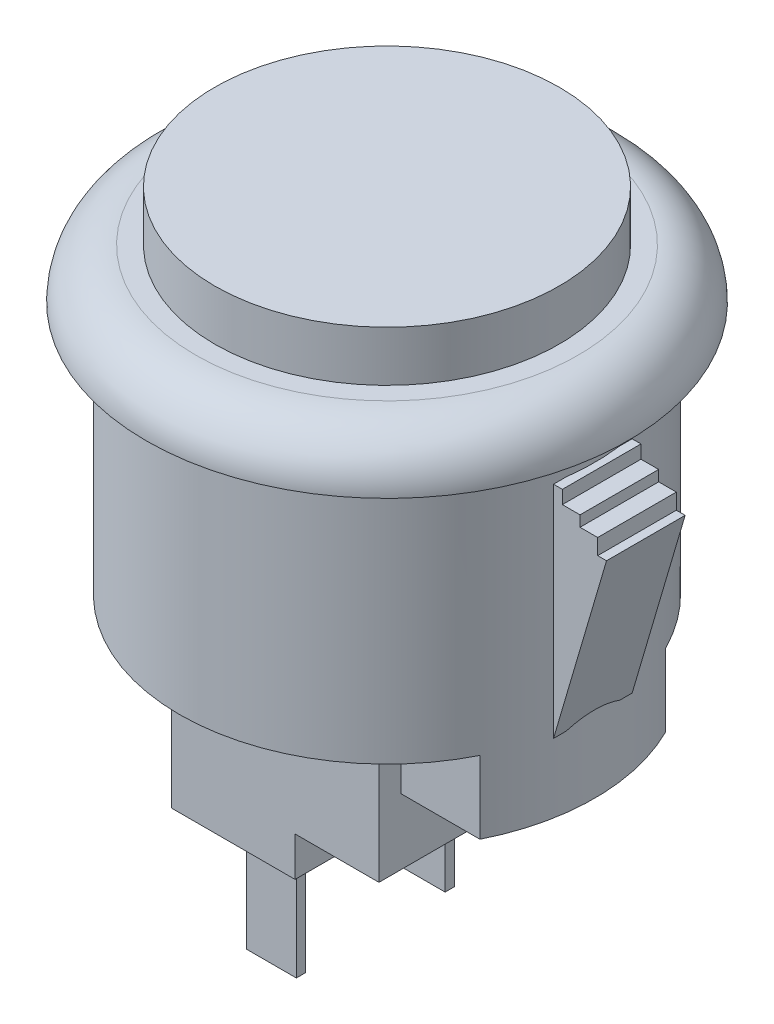
SolidWorks part; units mm, degrees
ref_plane "Front Plane" through (0, 0, 0) normal (0, 0, 1) x (1, 0, 0)
ref_plane "Top Plane" through (0, 0, 0) normal (0, 1, 0) x (1, 0, 0)
ref_plane "Right Plane" through (0, 0, 0) normal (1, 0, 0) x (0, 0, -1)
sketch "Sketch1" plane through (0, 0, 0) normal (0, 0, 1) x (1, 0, 0)
  line L0 (0, 0) -> (-11.75, 0)
  line L1 (-11.75, 0) -> (-11.75, 14.35)
  line L2 (-11.75, 14.35) -> (-13.625, 14.35)
  line L3 (-9.75, 17.15) -> (-9.75, 20)
  line L4 (-9.75, 20) -> (0, 20)
  line L5 (0, 20) -> (0, 0)
  line L6 (0, 0) -> (0, -2.2654) construction
  line L8 (-9.75, 17.15) -> (-10.825, 17.15)
  arc A0 (-13.625, 14.35) -> (-10.825, 17.15) centre (-10.825, 14.35) cw
  dimension "D1" = 23.5
  dimension "D2" = 27.25
  dimension "D3" = 19.5
  dimension "D4" = 14.35
  dimension "D5" = 20
  dimension "D6" = 2.85
revolve "Revolve1" add sketch "Sketch1" angle 360 about L6
sketch "Sketch2" plane through (0, 0, 0) normal (0, 0, 1) x (1, 0, 0)
  line L0 (-5.875, 0) -> (-5.875, -10.23)
  line L1 (-11.75, 0) -> (11.75, 0) construction
  line L2 (-5.875, -10.23) -> (1.125, -10.23)
  line L3 (1.125, -10.23) -> (1.125, -8)
  line L4 (1.125, -8) -> (5.875, -8)
  line L5 (5.875, -8) -> (5.875, 0)
  line L6 (5.875, 0) -> (-5.875, 0)
  line L7 (0, 0) -> (0, 3.0931) construction
  dimension "D1" = 10.23
  dimension "D2" = 8
  dimension "D3" = 7
  dimension "D4" = 11.75
extrude "Boss-Extrude1" add sketch "Sketch2" along normal mid plane 12.66
sketch "Sketch3" plane through (0, 0, 0) normal (0, -1, 0) x (1, 0, 0)
  line L0 (-10.5119, 5.25) -> (-6.0363, 5.25)
  line L1 (10.5119, -5.25) -> (6.0363, -5.25)
  line L2 (0, 0) -> (-1.7343, 0) construction
  line L3 (-6.0363, -5.25) -> (-10.5119, -5.25)
  line L4 (6.0363, 5.25) -> (10.5119, 5.25)
  arc A0 (-6.0363, 5.25) -> (-6.0363, -5.25) centre (0, 0) ccw
  circle A1 centre (0, 0) radius 11.75
  arc A2 (-10.5119, 5.25) -> (-10.5119, -5.25) centre (0, 0) ccw
  arc A3 (10.5119, -5.25) -> (10.5119, 5.25) centre (0, 0) ccw
  arc A4 (6.0363, -5.25) -> (6.0363, 5.25) centre (0, 0) ccw
  dimension "D3" = 8
  dimension "D2" = 10.5
  dimension "D1" = 0
extrude "Boss-Extrude2" add sketch "Sketch3" along normal blind 4.11
sketch "Sketch4" plane through (0, -10.23, 0) normal (0, -1, 0) x (1, 0, 0)
  line L0 (0, 0) -> (-3.137, 0) construction
  line L1 (-3.485, 4.475) -> (-0.655, 4.475)
  line L2 (-3.485, 4.475) -> (-3.485, 3.945)
  line L3 (-3.485, 3.945) -> (-0.655, 3.945)
  line L4 (-0.655, 4.475) -> (-0.655, 3.945)
  line L5 (-3.485, -3.945) -> (-0.655, -3.945)
  line L6 (-3.485, -3.945) -> (-3.485, -4.475)
  line L7 (-3.485, -4.475) -> (-0.655, -4.475)
  line L8 (-0.655, -3.945) -> (-0.655, -4.475)
  line L9 (-5.875, 6.33) -> (-5.875, -6.33) construction
  dimension "D1" = 2.83
  dimension "D2" = 0.53
  dimension "D3" = 2.39
  dimension "D4" = 8.95
extrude "Boss-Extrude3" add sketch "Sketch4" along normal blind 6.65
sketch "Sketch5" plane through (0, 0, 0) normal (0, 0, 1) x (1, 0, 0)
  line L0 (-11.65, -0.11) -> (-14.65, 10.1)
  line L2 (-14.65, 10.1) -> (-14.15, 10.1)
  line L3 (-14.15, 10.1) -> (-14.15, 10.99)
  line L4 (-14.15, 10.99) -> (-13.15, 10.99)
  line L5 (-13.15, 10.99) -> (-13.15, 11.6)
  line L6 (-13.15, 11.6) -> (-12.15, 11.6)
  line L7 (-12.15, 11.6) -> (-12.15, 12.35)
  line L8 (-12.15, 12.35) -> (-11.65, 12.35)
  line L9 (-11.65, 12.35) -> (-11.65, -0.11)
  line L10 (-13.625, 14.35) -> (13.625, 14.35) construction
  line L11 (-11.75, -4.11) -> (-10.5119, -4.11) construction
  line L12 (0, 0) -> (0, 3.9762) construction
  line L13 (-10.5119, 0) -> (10.5119, 0) construction
  line L14 (11.65, 12.35) -> (11.65, -0.11)
  line L15 (12.15, 12.35) -> (11.65, 12.35)
  line L16 (12.15, 11.6) -> (12.15, 12.35)
  line L17 (13.15, 11.6) -> (12.15, 11.6)
  line L18 (13.15, 10.99) -> (13.15, 11.6)
  line L19 (14.15, 10.99) -> (13.15, 10.99)
  line L20 (14.15, 10.1) -> (14.15, 10.99)
  line L21 (14.65, 10.1) -> (14.15, 10.1)
  line L22 (11.65, -0.11) -> (14.65, 10.1)
  line L23 (-11.75, 14.35) -> (-11.75, -4.11) construction
  dimension "D1" = 2
  dimension "D2" = 0.75
  dimension "D3" = 1.36
  dimension "D4" = 0.89
  dimension "D5" = 0.5
  dimension "D6" = 3
  dimension "D7" = 1
  dimension "D8" = 1
  dimension "D9" = 4
  dimension "D10" = 0.1
extrude "Boss-Extrude4" add sketch "Sketch5" along normal mid plane 4.45 separate body
combine bodies "Combine2" operation type add bodies to combine 106 105 104
